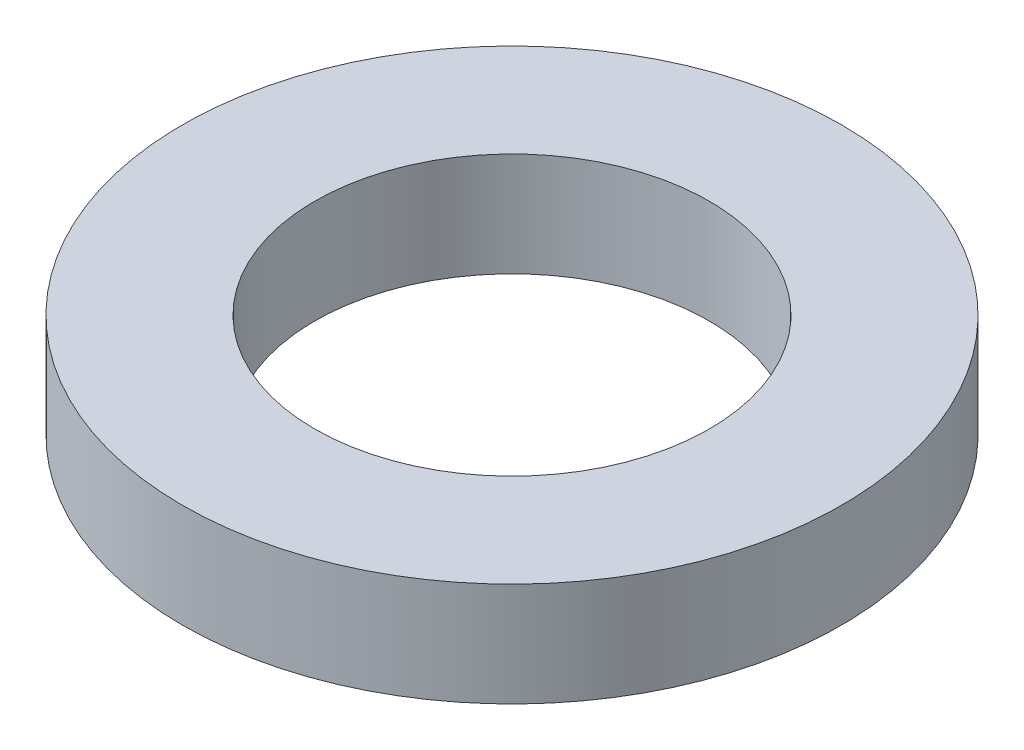
SolidWorks part; units mm, degrees
ref_plane "Front Plane" through (0, 0, 0) normal (0, 0, 1) x (1, 0, 0)
ref_plane "Top Plane" through (0, 0, 0) normal (0, 1, 0) x (1, 0, 0)
ref_plane "Right Plane" through (0, 0, 0) normal (1, 0, 0) x (0, 0, -1)
sketch "Sketch1" plane through (0, 0, 0) normal (0, 1, 0) x (1, 0, 0)
  circle A0 centre (0, 0) radius 3.802
  circle A1 centre (0, 0) radius 6.35
  dimension "D1" = 7.604
  dimension "D2" = 12.7
extrude "Boss-Extrude1" add sketch "Sketch1" along normal blind 2
